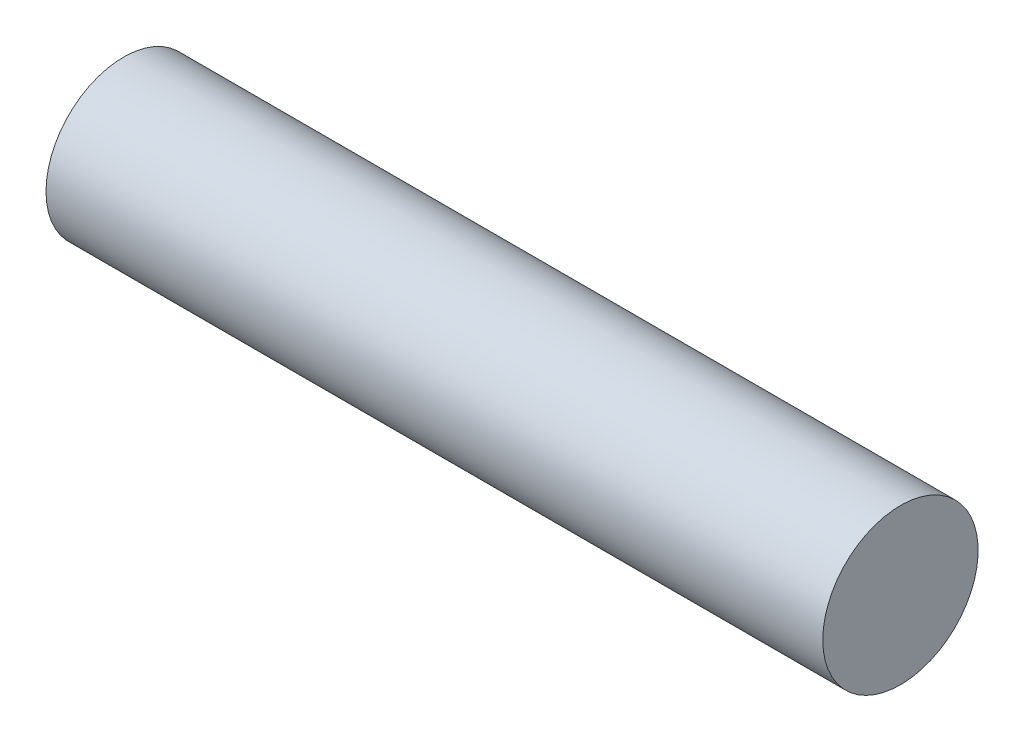
SolidWorks part; units mm, degrees
ref_plane "Спереди" through (0, 0, 0) normal (0, 0, 1) x (1, 0, 0)
ref_plane "Сверху" through (0, 0, 0) normal (0, 1, 0) x (1, 0, 0)
ref_plane "Справа" through (0, 0, 0) normal (1, 0, 0) x (0, 0, -1)
other "Configuration Table"
sketch "Эскиз1" plane through (0, 0, 0) normal (0, 1, 0) x (1, 0, 0)
  line L1 (-5, 0) -> (0, 0)
  line L2 (-5, 0) -> (-5, 0.5)
  line L3 (-5, 0.5) -> (0, 0.5)
  line L4 (0, 0) -> (0, 0.5)
  dimension "D1" = 5
  dimension "D2" = 0.5
revolve "Повернуть1" add sketch "Эскиз1" angle 360 about L1
